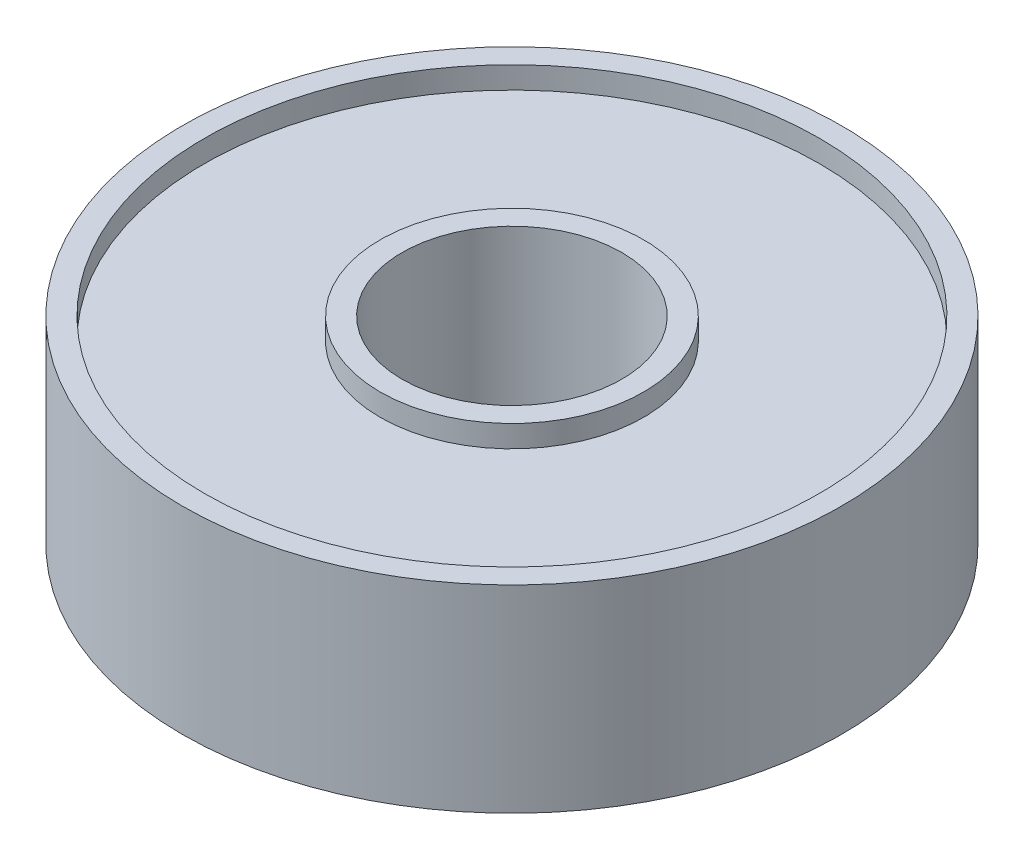
SolidWorks part; units mm, degrees
material "Chrome Stainless Steel"
ref_plane "Front Plane" through (0, 0, 0) normal (0, 0, 1) x (1, 0, 0)
ref_plane "Top Plane" through (0, 0, 0) normal (0, 1, 0) x (1, 0, 0)
ref_plane "Right Plane" through (0, 0, 0) normal (1, 0, 0) x (0, 0, -1)
sketch "Sketch1" plane through (0, 0, 0) normal (0, 1, 0) x (1, 0, 0)
  circle A0 centre (0, 0) radius 15
  dimension "D1" = 30
extrude "main extrusion" add sketch "Sketch1" along normal blind 9 contours A0
sketch "Sketch2" plane through (0, 9, 0) normal (0, 1, 0) x (1, 0, 0)
  circle A0 centre (0, 0) radius 5
  dimension "D1" = 10
extrude "ID bore" cut sketch "Sketch2" against normal blind 20
sketch "Sketch3" plane through (0, 9, 0) normal (0, 1, 0) x (1, 0, 0)
  circle A0 centre (0, 0) radius 14
  circle A1 centre (0, 0) radius 6
  dimension "D1" = 12
  dimension "D2" = 28
extrude "face recess" cut sketch "Sketch3" against normal blind 1
sketch "Sketch4" plane through (0, 0, 0) normal (0, -1, 0) x (1, 0, 0)
  circle A0 centre (0, 0) radius 14
  circle A1 centre (0, 0) radius 6
  dimension "D1" = 12
  dimension "D2" = 28
extrude "Cut-Extrude1" cut sketch "Sketch4" against normal blind 1
equation "\"D1@Sketch1\"=\"bearing OD\""
equation "\"D1@main extrusion\" = \"bearing depth\""
equation "\"D1@Sketch2\"=\"bearing ID\""
equation "\"motor mount pattern diameter\"= 30mm"
equation "\"D2@Sketch3\"=\"bearing OD\"-\"bearing outer race thickness\"*2"
equation "\"D1@Sketch3\"=\"bearing ID\"+\"bearing inner race thickness\"*2"
equation "\"D1@Sketch4\"=2*\"bearing inner race thickness\"+\"bearing ID\""
equation "\"D2@Sketch4\"=\"bearing OD\"-\"bearing outer race thickness\"*2"
equation "\"bearing OD\"= 30mm"
equation "\"bearing outer race thickness\"= 1mm"
equation "\"bearing ID\"= 10mm"
equation "\"bearing depth\"= 9mm"
equation "\"bearing inner race thickness\"= 1mm"
